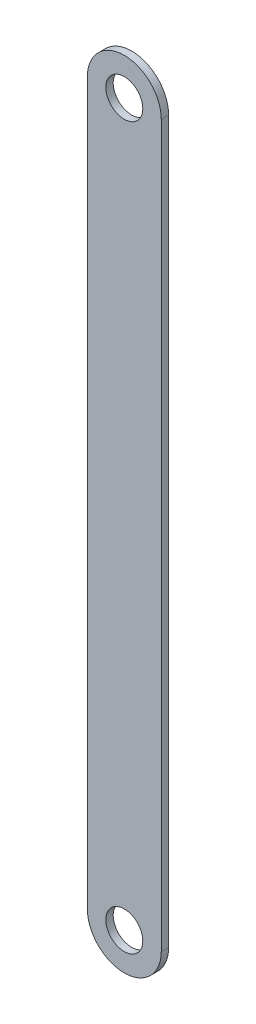
SolidWorks part; units mm, degrees
ref_plane "Спереди" through (0, 0, 0) normal (0, 0, 1) x (1, 0, 0)
ref_plane "Сверху" through (0, 0, 0) normal (0, 1, 0) x (1, 0, 0)
ref_plane "Справа" through (0, 0, 0) normal (1, 0, 0) x (0, 0, -1)
sketch "Эскиз1" plane through (0, 0, 0) normal (0, 0, 1) x (1, 0, 0)
  line L4 (-5, 97.5) -> (-5, 0)
  line L5 (5, 97.5) -> (5, 0)
  circle A0 centre (0, 0) radius 2.5
  circle A2 centre (0, 97.5) radius 2.5
  arc A7 (5, 97.5) -> (-5, 97.5) centre (0, 97.5) ccw
  arc A8 (-5, 0) -> (5, 0) centre (0, 0) ccw
  point P17 (0, 65)
  dimension "D1" = 97.5
  dimension "D2" = 5
  dimension "D3" = 10
  dimension "D4" = 5
extrude "Бобышка-Вытянуть1" add sketch "Эскиз1" along normal blind 1
